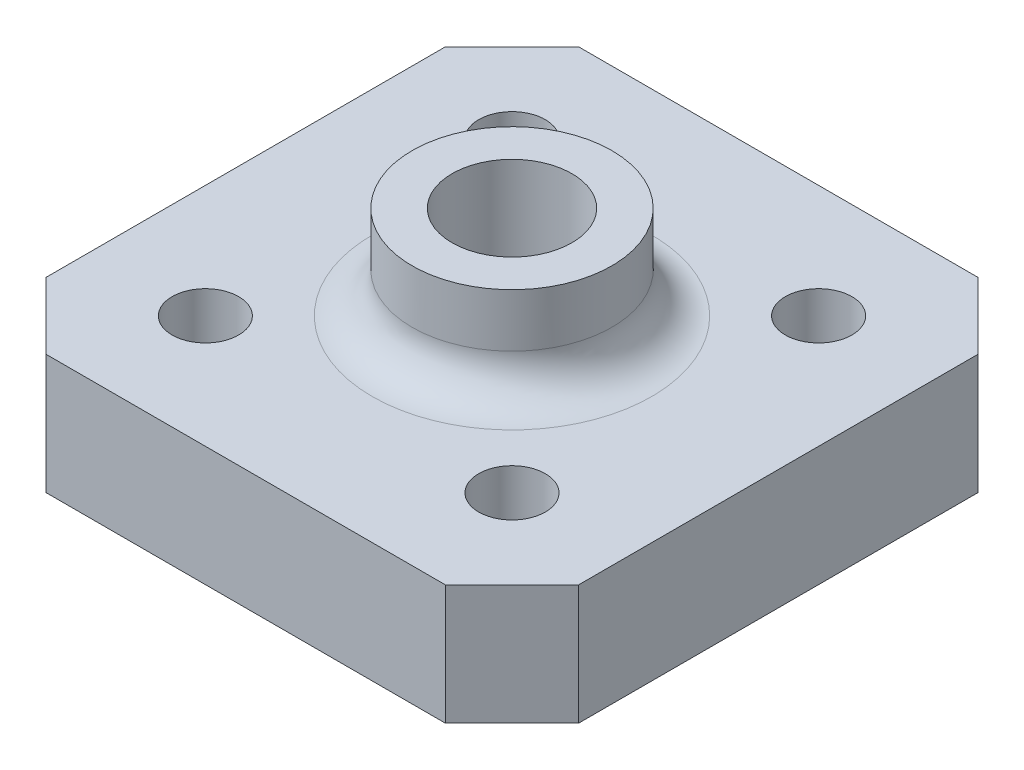
SolidWorks part; units mm, degrees
ref_plane "Front Plane" through (0, 0, 0) normal (0, 0, 1) x (1, 0, 0)
ref_plane "Top Plane" through (0, 0, 0) normal (0, 1, 0) x (1, 0, 0)
ref_plane "Right Plane" through (0, 0, 0) normal (1, 0, 0) x (0, 0, -1)
sketch "Sketch1" plane through (0, 0, 0) normal (0, 1, 0) x (1, 0, 0)
  line L1 (-20, 20) -> (20, 20)
  line L2 (-20, 20) -> (-20, -20)
  line L3 (-20, -20) -> (20, -20)
  line L4 (20, 20) -> (20, -20)
  line L5 (-20, 20) -> (20, -20) construction
  line L6 (-20, -20) -> (20, 20) construction
  line L7 (7.5056, 0) -> (3.7528, 6.5)
  line L8 (3.7528, 6.5) -> (-3.7528, 6.5)
  line L9 (-3.7528, 6.5) -> (-7.5056, 0)
  line L10 (-7.5056, 0) -> (-3.7528, -6.5)
  line L11 (-3.7528, -6.5) -> (3.7528, -6.5)
  line L12 (3.7528, -6.5) -> (7.5056, 0)
  circle A0 centre (0, 0) radius 6.5 construction
  point P0 (0, 0)
  dimension "D2" = 13
  dimension "D1" = 40
extrude "Boss-Extrude1" add sketch "Sketch1" along normal blind 6
sketch "Sketch2" plane through (0, 6, 0) normal (0, 1, 0) x (1, 0, 0)
  line L1 (-20, 20) -> (20, 20)
  line L2 (-20, 20) -> (-20, -20)
  line L3 (-20, -20) -> (20, -20)
  line L4 (20, 20) -> (20, -20)
  circle A0 centre (0, 0) radius 4.5
  dimension "D1" = 9
extrude "Boss-Extrude2" add sketch "Sketch2" along normal blind 3
sketch "Sketch3" plane through (0, 9, 0) normal (0, 1, 0) x (1, 0, 0)
  line L0 (-20, 20) -> (20, -20) construction
  line L1 (-20, -20) -> (20, 20) construction
  circle A0 centre (-11.5147, 11.5147) radius 2.5
  circle A1 centre (11.5147, 11.5147) radius 2.5
  circle A2 centre (11.5147, -11.5147) radius 2.5
  circle A3 centre (-11.5147, -11.5147) radius 2.5
  dimension "D1" = 5
  dimension "D2" = 12
  dimension "D3" = 12
  dimension "D4" = 12
  dimension "D5" = 12
extrude "Cut-Extrude1" cut sketch "Sketch3" against normal blind 24
sketch "Sketch4" plane through (0, 9, 0) normal (0, 1, 0) x (1, 0, 0)
  circle A0 centre (0, 0) radius 4.5
  circle A1 centre (0, 0) radius 7.5
  dimension "D1" = 3
extrude "Boss-Extrude3" add sketch "Sketch4" along normal blind 7
fillet "Fillet1" radius 3 1 edges at (0, 9, 7.5)
chamfer "Chamfer1" distance 5 angle 45 4 edges at (-20, 4.5, -20) (-20, 4.5, 20) (20, 4.5, 20) (20, 4.5, -20)
